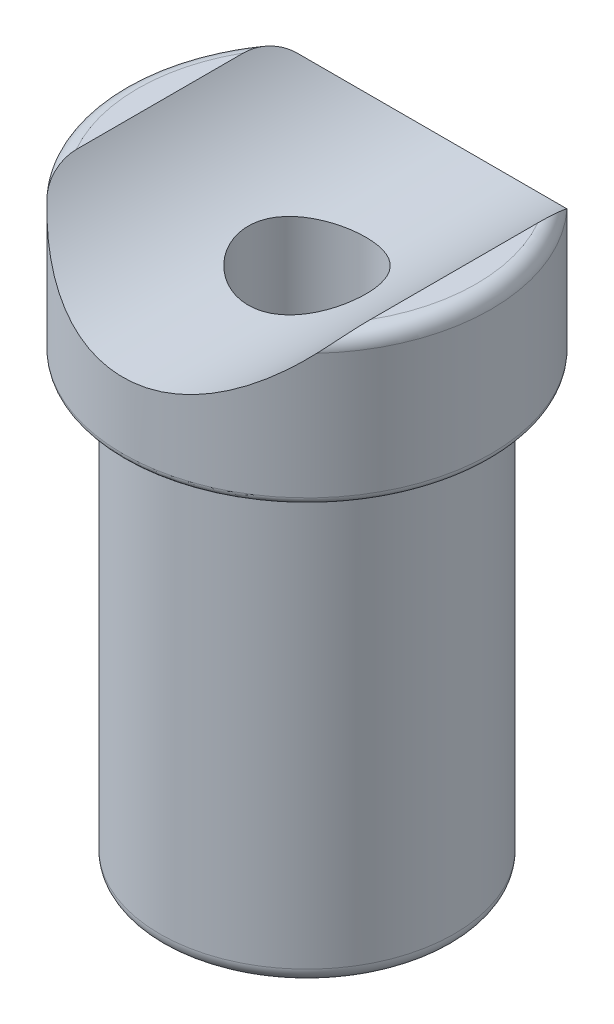
SolidWorks part; units mm, degrees
ref_plane "Спереди" through (0, 0, 0) normal (0, 0, 1) x (1, 0, 0)
ref_plane "Сверху" through (0, 0, 0) normal (0, 1, 0) x (1, 0, 0)
ref_plane "Справа" through (0, 0, 0) normal (1, 0, 0) x (0, 0, -1)
sketch "Эскиз1" plane through (0, 0, 0) normal (0, 0, 1) x (1, 0, 0)
  line L0 (0, 98.8343) -> (0, -81.2807) construction
  line L1 (-4, 33) -> (-4, 16)
  line L2 (-4, 16) -> (-7, 16)
  line L3 (-7, 16) -> (-7, -7)
  line L4 (-7, -7) -> (-10, -7)
  line L5 (-10, -7) -> (-10, 23)
  line L6 (-10, 23) -> (-12.5, 23)
  line L7 (-12.5, 23) -> (-12.5, 33)
  line L8 (-12.5, 33) -> (-4, 33)
  dimension "D1" = 4
  dimension "D2" = 7
  dimension "D3" = 23
  dimension "D4" = 40
  dimension "D5" = 7
  dimension "D6" = 3
  dimension "D7" = 10
  dimension "D8" = 12.5
revolve "Повернуть1" add sketch "Эскиз1" angle 360 about L0
sketch "Эскиз2" plane through (0, 0, 0) normal (0, 0, 1) x (1, 0, 0)
  line L0 (-10, 23) -> (10, 23) construction
  circle A0 centre (0, 40.5) radius 12.5
  dimension "D1" = 17.5
  dimension "D2" = 25
extrude "Вырез-Вытянуть1" cut sketch "Эскиз2" against normal through all and the other way through all
fillet "Скругление1" radius 1 4 edges at (12.5, 33, 0) (-12.5, 33, 0) (0, 28, 12.5) (0, 28, -12.5)
fillet "Скругление2" radius 0.5 1 edges at (0, 23, 12.5)
fillet "Скругление3" radius 1 2 edges at (0, -7, 7) (0, -7, 10)
